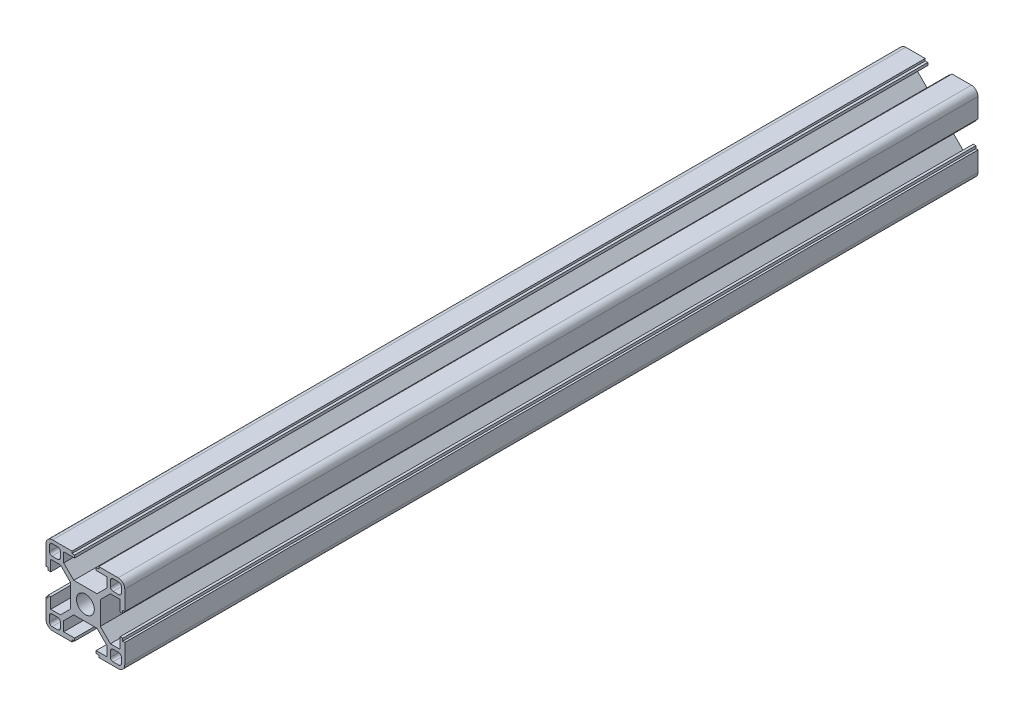
SolidWorks part; units mm, degrees
material "6061-T6 (SS)"
ref_plane "前视基准面" through (0, 0, 0) normal (0, 0, 1) x (1, 0, 0)
ref_plane "上视基准面" through (0, 0, 0) normal (0, 1, 0) x (1, 0, 0)
ref_plane "右视基准面" through (0, 0, 0) normal (1, 0, 0) x (0, 0, -1)
sketch "Sketch1" plane through (0, 0, 0) normal (0, 0, 1) x (1, 0, 0)
  line L0 (-5.1, 15) -> (-5.1, 14.2)
  line L1 (-12.5, -15) -> (12.5, -15)
  line L2 (-15, -12.5) -> (-15, 12.5)
  line L3 (-12.5, 15) -> (12.5, 15)
  line L4 (15, -12.5) -> (15, 12.5)
  line L5 (-15, -15) -> (15, 15) construction
  line L6 (-15, 15) -> (15, -15) construction
  line L7 (-5.1, 14.2) -> (-4.1, 14.2)
  line L8 (-4.1, 14.2) -> (-4.1, 13.2)
  line L9 (-4.1, 13.2) -> (-8.25, 13.2)
  line L10 (-8.25, 13.2) -> (-8.25, 9.5228)
  line L11 (-8.25, 9.5228) -> (-4.4272, 5.7)
  line L12 (-4.4272, 5.7) -> (4.4272, 5.7)
  line L13 (-5.1, 15) -> (5.1, 15)
  line L14 (0, 15) -> (0, 5.7) construction
  line L15 (8.25, 9.5228) -> (4.4272, 5.7)
  line L16 (8.25, 13.2) -> (8.25, 9.5228)
  line L17 (4.1, 13.2) -> (8.25, 13.2)
  line L18 (4.1, 14.2) -> (4.1, 13.2)
  line L19 (5.1, 14.2) -> (4.1, 14.2)
  line L20 (5.1, 15) -> (5.1, 14.2)
  line L21 (15, 5.1) -> (14.2, 5.1)
  line L22 (14.2, 5.1) -> (14.2, 4.1)
  line L23 (14.2, 4.1) -> (13.2, 4.1)
  line L24 (13.2, 4.1) -> (13.2, 8.25)
  line L25 (13.2, 8.25) -> (9.5228, 8.25)
  line L26 (9.5228, 8.25) -> (5.7, 4.4272)
  line L27 (5.7, 4.4272) -> (5.7, -4.4272)
  line L28 (15, 5.1) -> (15, -5.1)
  line L29 (9.5228, -8.25) -> (5.7, -4.4272)
  line L30 (13.2, -8.25) -> (9.5228, -8.25)
  line L31 (13.2, -4.1) -> (13.2, -8.25)
  line L32 (14.2, -4.1) -> (13.2, -4.1)
  line L33 (14.2, -5.1) -> (14.2, -4.1)
  line L34 (15, -5.1) -> (14.2, -5.1)
  line L35 (15, 0) -> (5.7, 0) construction
  line L36 (5.1, -15) -> (5.1, -14.2)
  line L37 (5.1, -14.2) -> (4.1, -14.2)
  line L38 (4.1, -14.2) -> (4.1, -13.2)
  line L39 (4.1, -13.2) -> (8.25, -13.2)
  line L40 (8.25, -13.2) -> (8.25, -9.5228)
  line L41 (8.25, -9.5228) -> (4.4272, -5.7)
  line L42 (4.4272, -5.7) -> (-4.4272, -5.7)
  line L43 (5.1, -15) -> (-5.1, -15)
  line L44 (-8.25, -9.5228) -> (-4.4272, -5.7)
  line L45 (-8.25, -13.2) -> (-8.25, -9.5228)
  line L46 (-4.1, -13.2) -> (-8.25, -13.2)
  line L47 (-4.1, -14.2) -> (-4.1, -13.2)
  line L48 (-5.1, -14.2) -> (-4.1, -14.2)
  line L49 (-5.1, -15) -> (-5.1, -14.2)
  line L50 (0, -15) -> (0, -5.7) construction
  line L51 (-15, -5.1) -> (-14.2, -5.1)
  line L52 (-14.2, -5.1) -> (-14.2, -4.1)
  line L53 (-14.2, -4.1) -> (-13.2, -4.1)
  line L54 (-13.2, -4.1) -> (-13.2, -8.25)
  line L55 (-13.2, -8.25) -> (-9.5228, -8.25)
  line L56 (-9.5228, -8.25) -> (-5.7, -4.4272)
  line L57 (-5.7, -4.4272) -> (-5.7, 4.4272)
  line L58 (-15, -5.1) -> (-15, 5.1)
  line L59 (-9.5228, 8.25) -> (-5.7, 4.4272)
  line L60 (-13.2, 8.25) -> (-9.5228, 8.25)
  line L61 (-13.2, 4.1) -> (-13.2, 8.25)
  line L62 (-14.2, 4.1) -> (-13.2, 4.1)
  line L63 (-14.2, 5.1) -> (-14.2, 4.1)
  line L64 (-15, 5.1) -> (-14.2, 5.1)
  line L65 (-15, 0) -> (-5.7, 0) construction
  line L66 (0, 0) -> (0, 5.7) construction
  circle A0 centre (0, 0) radius 3.4
  arc A1 (-12.5, -15) -> (-15, -12.5) centre (-12.5, -12.5) cw
  arc A2 (12.5, -15) -> (15, -12.5) centre (12.5, -12.5) ccw
  arc A3 (12.5, 15) -> (15, 12.5) centre (12.5, 12.5) cw
  arc A4 (-15, 12.5) -> (-12.5, 15) centre (-12.5, 12.5) cw
  point P0 (0, 0)
  dimension "D3" = 6.8
  dimension "D12" = 2.5
  dimension "D1" = 30
  dimension "D2" = 30
  dimension "D4" = 16.5
  dimension "D5" = 8.2
  dimension "D6" = 10.2
  dimension "D7" = 7.5
  dimension "D9" = 1.8
  dimension "D10" = 1.8
  dimension "D11" = 0.8
  dimension "D8" = 4
extrude "Extrude1" add sketch "Sketch1" along normal blind 325 contours A4 L2 L64 L63 L62 L61 L60 L59 L57 L56 L55 L54 L53 L52 L51 A1 L1 L49 L48 L47 L46 L45 L44 L42 L41 L40 L39 L38 L37 L36 A2 L4 L34 L33 L32 L31 L30 L29 L27 L26 L25 L24 L23 L22 L21 A3 L3 L20
sketch "Sketch2" plane through (0, 0, 325) normal (0, 0, 1) x (1, 0, 0)
  line L0 (13.7, 12.7) -> (13.7, 10.55)
  line L1 (-12.7, 13.7) -> (-10.55, 13.7)
  line L2 (-13.7, 12.7) -> (-13.7, 10.55)
  line L3 (-12.7, 9.55) -> (-10.55, 9.55)
  line L4 (-9.55, 12.7) -> (-9.55, 10.55)
  line L5 (-13.7, 13.7) -> (-9.55, 9.55) construction
  line L6 (-13.7, 9.55) -> (-9.55, 13.7) construction
  line L7 (12.7, 13.7) -> (10.55, 13.7)
  line L8 (9.55, 12.7) -> (9.55, 10.55)
  line L9 (12.7, 9.55) -> (10.55, 9.55)
  line L10 (12.7, -13.7) -> (10.55, -13.7)
  line L11 (13.7, -12.7) -> (13.7, -10.55)
  line L12 (12.7, -9.55) -> (10.55, -9.55)
  line L13 (9.55, -12.7) -> (9.55, -10.55)
  line L14 (-13.7, -12.7) -> (-13.7, -10.55)
  line L15 (-12.7, -13.7) -> (-10.55, -13.7)
  line L16 (-9.55, -12.7) -> (-9.55, -10.55)
  line L17 (-12.7, -9.55) -> (-10.55, -9.55)
  line L18 (0, 0) -> (-9.55, 9.55) construction
  line L19 (-12.5, 15) -> (-5.1, 15) construction
  line L20 (-15, 5.1) -> (-15, 12.5) construction
  line L21 (-13.2, 8.25) -> (-9.5228, 8.25) construction
  line L22 (-8.25, 13.2) -> (-8.25, 9.5228) construction
  arc A0 (-13.7, -12.7) -> (-12.7, -13.7) centre (-12.7, -12.7) ccw
  arc A1 (-10.55, -13.7) -> (-9.55, -12.7) centre (-10.55, -12.7) ccw
  arc A2 (-9.55, -10.55) -> (-10.55, -9.55) centre (-10.55, -10.55) ccw
  arc A3 (-13.7, -10.55) -> (-12.7, -9.55) centre (-12.7, -10.55) cw
  arc A4 (13.7, -10.55) -> (12.7, -9.55) centre (12.7, -10.55) ccw
  arc A5 (12.7, -13.7) -> (13.7, -12.7) centre (12.7, -12.7) ccw
  arc A6 (10.55, -13.7) -> (9.55, -12.7) centre (10.55, -12.7) cw
  arc A7 (10.55, -9.55) -> (9.55, -10.55) centre (10.55, -10.55) ccw
  arc A8 (13.7, 12.7) -> (12.7, 13.7) centre (12.7, 12.7) ccw
  arc A9 (13.7, 10.55) -> (12.7, 9.55) centre (12.7, 10.55) cw
  arc A10 (9.55, 10.55) -> (10.55, 9.55) centre (10.55, 10.55) ccw
  arc A11 (10.55, 13.7) -> (9.55, 12.7) centre (10.55, 12.7) ccw
  arc A12 (-10.55, 13.7) -> (-9.55, 12.7) centre (-10.55, 12.7) cw
  arc A13 (-10.55, 9.55) -> (-9.55, 10.55) centre (-10.55, 10.55) ccw
  arc A14 (-13.7, 10.55) -> (-12.7, 9.55) centre (-12.7, 10.55) ccw
  arc A15 (-12.7, 13.7) -> (-13.7, 12.7) centre (-12.7, 12.7) ccw
  point P0 (-11.625, 11.625)
  dimension "D2" = 1
  dimension "D3" = 1.3
  dimension "D4" = 1.3
  dimension "D5" = 1.3
  dimension "D6" = 1.3
  dimension "D1" = 4
extrude "Extrude2" cut sketch "Sketch2" against normal through all
